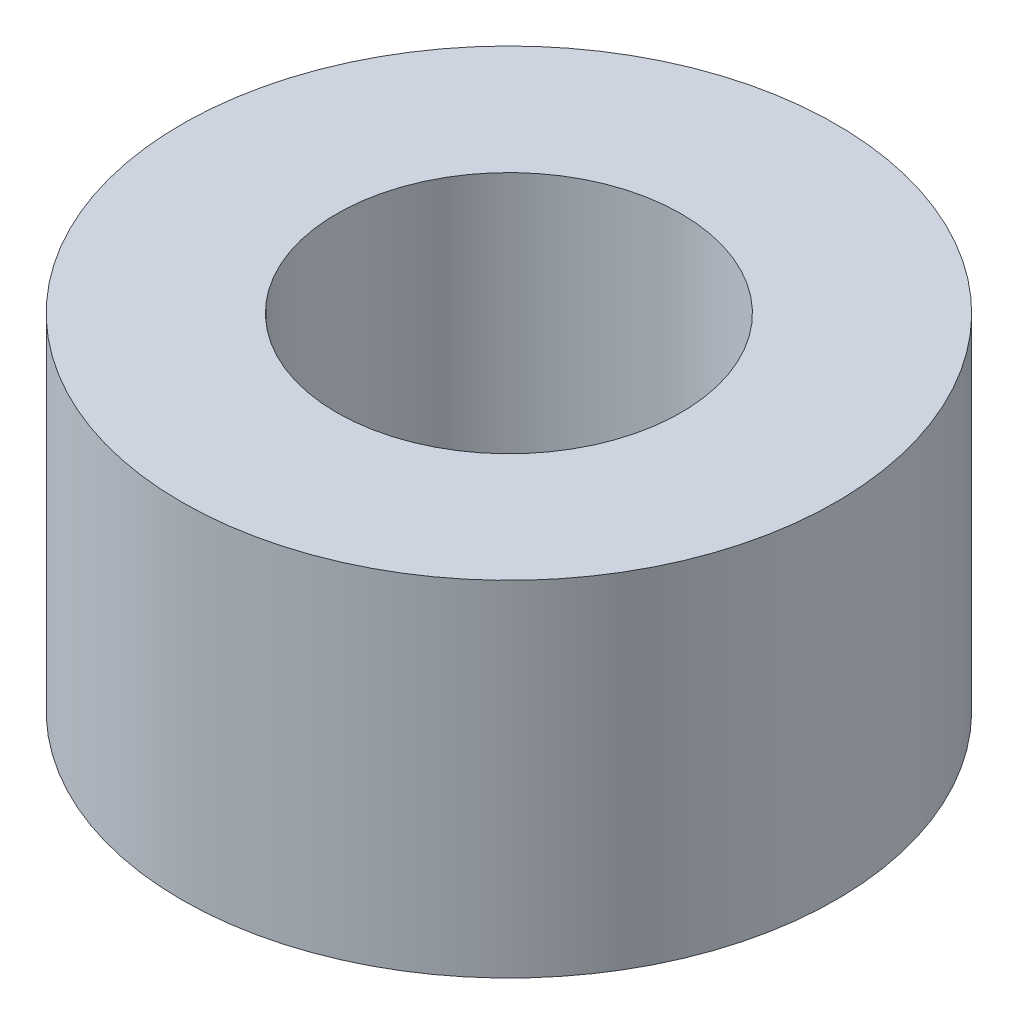
SolidWorks part; units mm, degrees
ref_plane "前视基准面" through (0, 0, 0) normal (0, 0, 1) x (1, 0, 0)
ref_plane "上视基准面" through (0, 0, 0) normal (0, 1, 0) x (1, 0, 0)
ref_plane "右视基准面" through (0, 0, 0) normal (1, 0, 0) x (0, 0, -1)
other "Configuration Table"
sketch "草图1" plane through (0, 0, 0) normal (0, 1, 0) x (1, 0, 0)
  circle A0 centre (0, 0) radius 5
  circle A1 centre (0, 0) radius 9.5
  dimension "D1" = 10
  dimension "D2" = 19
extrude "凸台-拉伸1" add sketch "草图1" along normal blind 10
